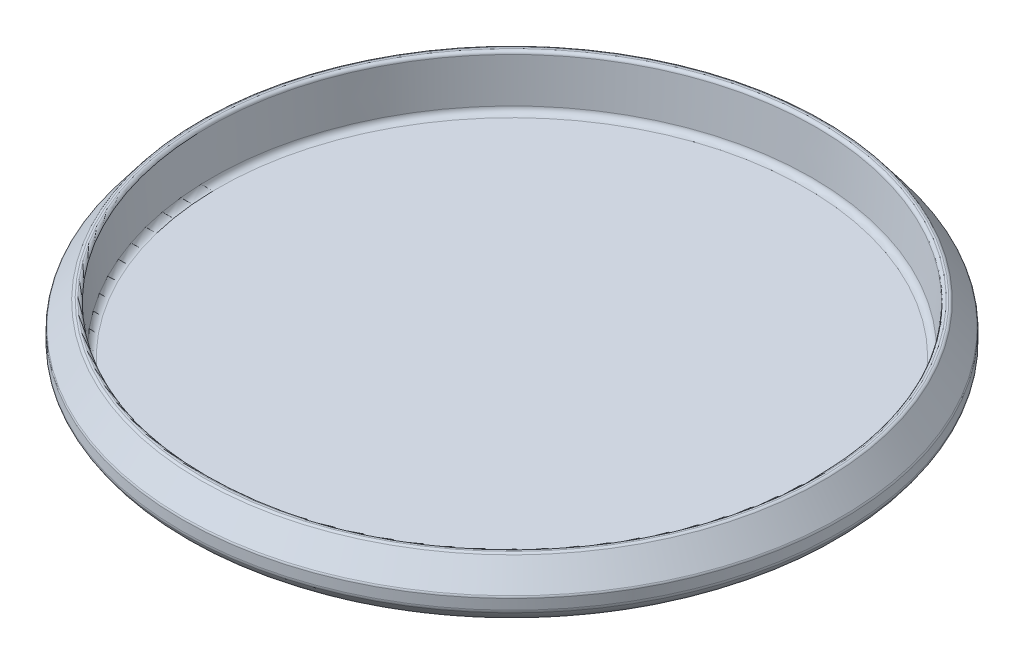
SolidWorks part; units mm, degrees
ref_plane "Front (XY)" through (0, 0, 0) normal (0, 0, 1) x (1, 0, 0)
ref_plane "Top (XZ)" through (0, 0, 0) normal (0, 1, 0) x (1, 0, 0)
ref_plane "Right (YZ)" through (0, 0, 0) normal (1, 0, 0) x (0, 0, -1)
sketch "Sketch1" plane through (0, 0, 0) normal (0, 1, 0) x (1, 0, 0)
  circle A0 centre (0, 0) radius 95
  dimension "D1" = 190
extrude "Boss-Extrude1" add sketch "Sketch1" along normal blind 1.5
sketch "Sketch2" plane through (0, 0, 0) normal (0, 0, 1) x (1, 0, 0)
  line L0 (95, 0) -> (106, 0) construction
  line L1 (95, 1.5) -> (96.4042, 17.55)
  line L2 (95, 0) -> (95, 1.5) construction
  line L3 (96.4042, 17.55) -> (98.4042, 17.55)
  line L4 (98.4042, 17.55) -> (98.4042, 8.55) construction
  line L5 (98.4042, 17.55) -> (104.4611, 9.593)
  line L6 (104.4611, 9.593) -> (104.4611, 5.593)
  line L8 (95, 1.5) -> (95, 0)
  line L9 (0, 0) -> (0, 11.5081) construction
  arc A0 (95, 0) -> (104.4611, 5.593) centre (95.7578, 9.5168) ccw
  dimension "D1" = 11
  dimension "D2" = 16.05
  dimension "D3" = 185
  dimension "D4" = 2
  dimension "D5" = 9
  dimension "D6" = 10
  dimension "D7" = 4
revolve "Revolve1" add sketch "Sketch2" angle 360 about L9
fillet "Fillet1" radius 1 2 edges at (0, 17.55, -96.4042) (0, 17.55, -98.4042)
fillet "Fillet2" radius 1 1 edges at (0, 9.593, -104.4611)
fillet "Fillet4" radius 2 1 edges at (0, 5.593, -104.4611)
fillet "Fillet5" radius 2 1 edges at (0, 1.5, -95)
